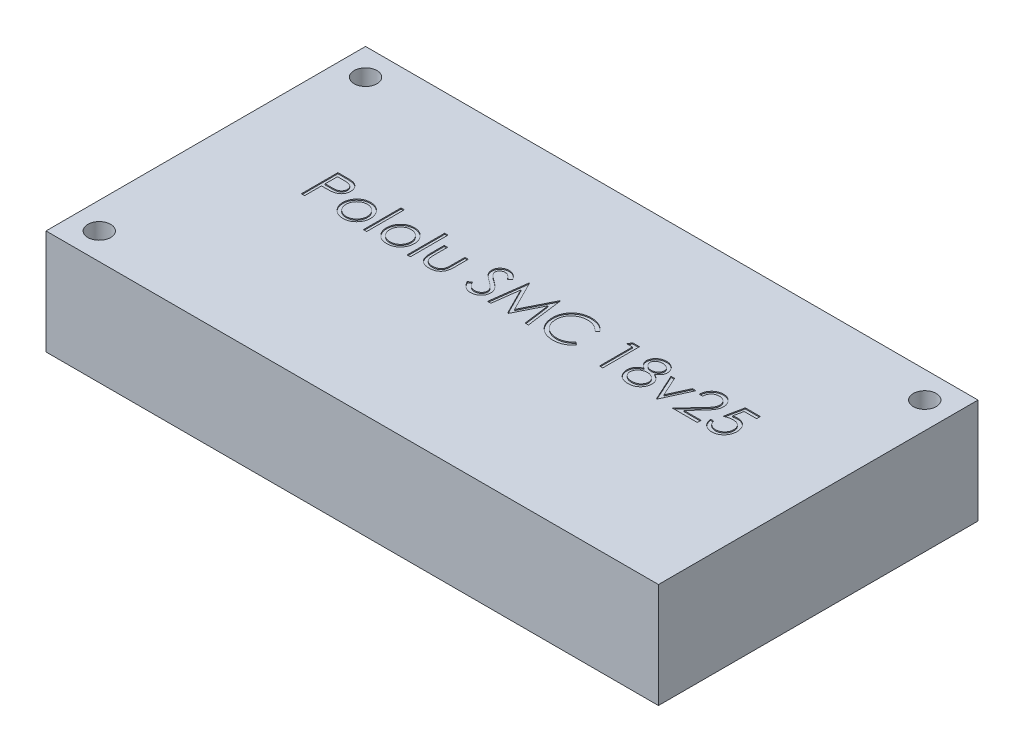
SolidWorks part; units mm, degrees
ref_plane "Front Plane" through (0, 0, 0) normal (0, 0, 1) x (1, 0, 0)
ref_plane "Top Plane" through (0, 0, 0) normal (0, 1, 0) x (1, 0, 0)
ref_plane "Right Plane" through (0, 0, 0) normal (1, 0, 0) x (0, 0, -1)
sketch "Sketch1" plane through (0, 0, 0) normal (0, 1, 0) x (1, 0, 0)
  line L1 (-29.21, -15.24) -> (29.21, -15.24)
  line L2 (-29.21, -15.24) -> (-29.21, 15.24)
  line L3 (-29.21, 15.24) -> (29.21, 15.24)
  line L4 (29.21, -15.24) -> (29.21, 15.24)
  line L5 (-29.21, -15.24) -> (29.21, 15.24) construction
  line L6 (-29.21, 15.24) -> (29.21, -15.24) construction
  point P0 (0, 0)
  dimension "D1" = 30.48
  dimension "D2" = 58.42
extrude "Boss-Extrude1" add sketch "Sketch1" along normal blind 10
sketch "Sketch2" plane through (0, 10, 0) normal (0, 1, 0) x (1, 0, 0)
  line L0 (-29.21, -15.24) -> (29.21, -15.24) construction
  line L2 (-29.21, 15.24) -> (-29.21, -15.24) construction
  line L3 (29.21, 15.24) -> (-29.21, 15.24) construction
  line L4 (29.21, -15.24) -> (29.21, 15.24) construction
  circle A0 centre (-26.67, 12.7) radius 1.0922
  circle A1 centre (-26.67, -12.7) radius 1.0922
  circle A2 centre (26.67, 12.7) radius 1.0922
  dimension "D3" = 2.1844
  dimension "D1" = 2.54
  dimension "D2" = 2.54
  dimension "D4" = 2.54
  dimension "D5" = 2.54
extrude "Cut-Extrude1" cut sketch "Sketch2" against normal through all
sketch "Sketch3" plane through (0, 10, 0) normal (0, 1, 0) x (1, 0, 0)
  line L0 (-29.21, 0) -> (29.21, 0) construction
  line L1 (-29.21, 15.24) -> (-29.21, -15.24) construction
  line L2 (29.21, -15.24) -> (29.21, 15.24) construction
  text T0 "Pololu SMC 18v25"
extrude "Cut-Extrude2" cut sketch "Sketch3" against normal blind 0.1
